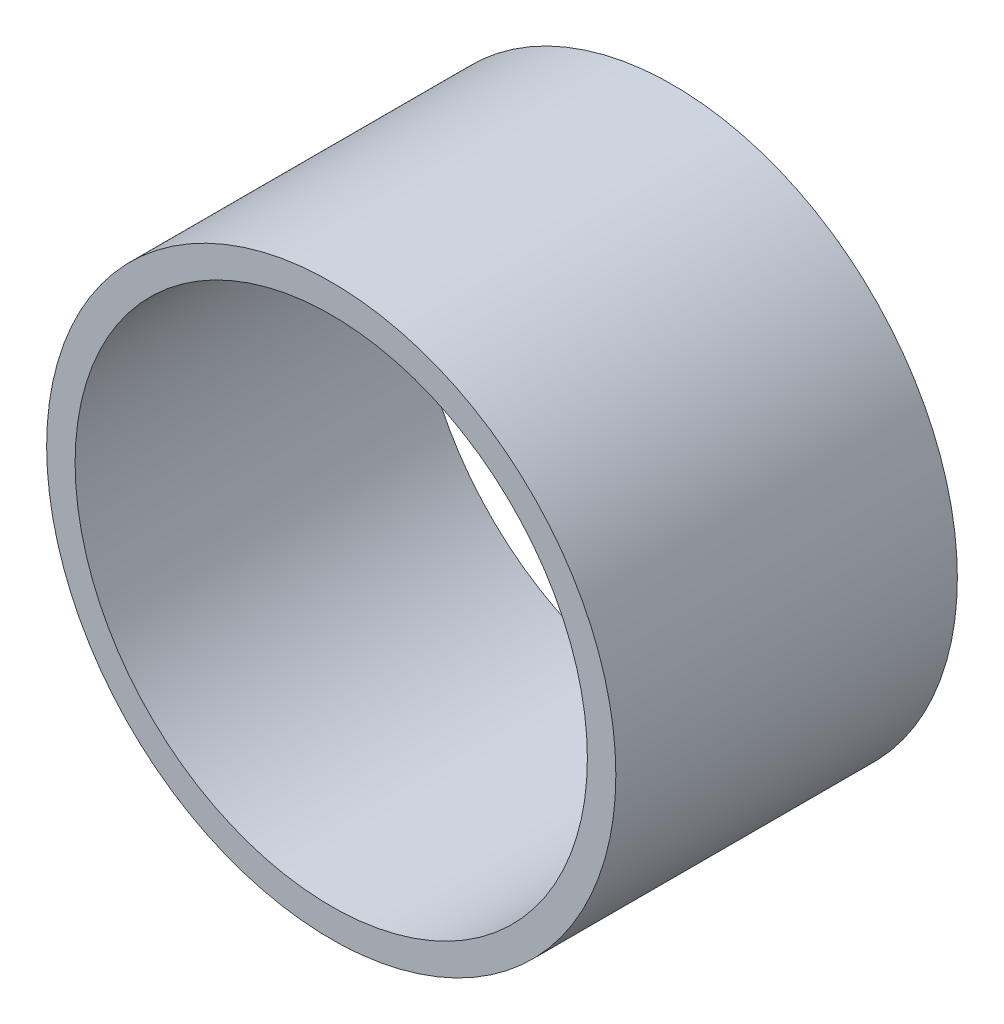
SolidWorks part; units mm, degrees
ref_plane "Plan de face" through (0, 0, 0) normal (0, 0, 1) x (1, 0, 0)
ref_plane "Plan de dessus" through (0, 0, 0) normal (0, 1, 0) x (1, 0, 0)
ref_plane "Plan de droite" through (0, 0, 0) normal (1, 0, 0) x (0, 0, -1)
sketch "Esquisse1" plane through (0, 0, 0) normal (0, 0, 1) x (1, 0, 0)
  circle A0 centre (0, 0) radius 22.5
  circle A1 centre (0, 0) radius 25
  dimension "D1" = 45
  dimension "D2" = 50
extrude "Boss.-Extru.1" add sketch "Esquisse1" along normal blind 30
